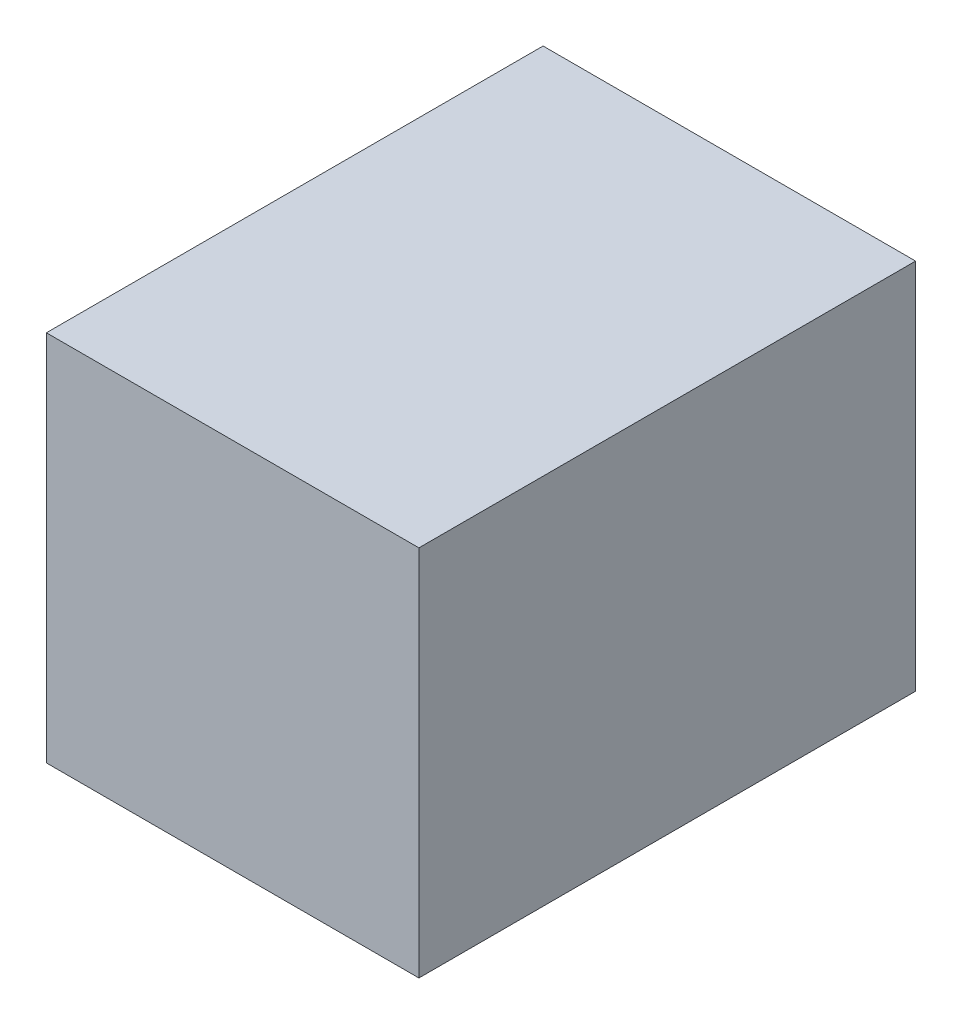
SolidWorks part; units mm, degrees
material "Plain Carbon Steel"
ref_plane "Front Plane" through (0, 0, 0) normal (0, 0, 1) x (1, 0, 0)
ref_plane "Top Plane" through (0, 0, 0) normal (0, 1, 0) x (1, 0, 0)
ref_plane "Right Plane" through (0, 0, 0) normal (1, 0, 0) x (0, 0, -1)
sketch "Sketch1" plane through (0, 0, 0) normal (0, 0, 1) x (1, 0, 0)
  line L1 (-15, -15) -> (15, -15)
  line L2 (-15, -15) -> (-15, 15)
  line L3 (-15, 15) -> (15, 15)
  line L4 (15, -15) -> (15, 15)
  line L5 (-15, -15) -> (15, 15) construction
  line L6 (-15, 15) -> (15, -15) construction
  point P0 (0, 0)
  dimension "D1" = 30
  dimension "D2" = 30
extrude "Boss-Extrude1" add sketch "Sketch1" along normal blind 40
